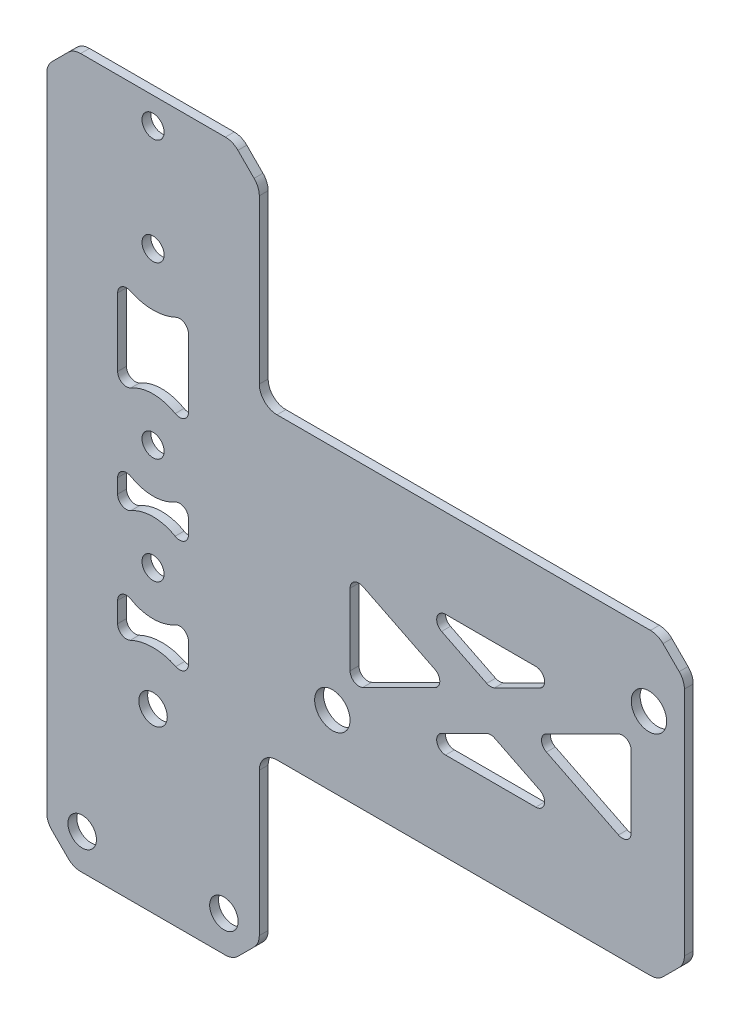
SolidWorks part; units mm, degrees
ref_plane "Front Plane" through (0, 0, 0) normal (0, 0, 1) x (1, 0, 0)
ref_plane "Top Plane" through (0, 0, 0) normal (0, 1, 0) x (1, 0, 0)
ref_plane "Right Plane" through (0, 0, 0) normal (1, 0, 0) x (0, 0, -1)
sketch "Sketch1" plane through (0, 0, 0) normal (0, 0, 1) x (1, 0, 0)
  line L1 (-19.05, 63.5) -> (19.05, 63.5)
  line L2 (-19.05, 63.5) -> (-19.05, -63.5)
  line L3 (-19.05, -63.5) -> (19.05, -63.5)
  line L4 (19.05, 63.5) -> (19.05, -63.5)
  line L5 (-19.05, 63.5) -> (19.05, -63.5) construction
  line L6 (-19.05, -63.5) -> (19.05, 63.5) construction
  line L7 (19.05, 25.019) -> (95.25, 25.019)
  line L8 (19.05, 25.019) -> (19.05, -28.575)
  line L9 (19.05, -28.575) -> (95.25, -28.575)
  line L10 (95.25, 25.019) -> (95.25, -28.575)
  circle A0 centre (32.1437, -15.875) radius 3.175
  circle A1 centre (88.9, 12.319) radius 3.175
  point P0 (0, 0)
  dimension "D7" = 6.35
  dimension "D1" = 34.925
  dimension "D2" = 38.1
  dimension "D3" = 76.2
  dimension "D4" = 127
  dimension "D5" = 6.35
  dimension "D6" = 12.7
  dimension "D8" = 12.7
  dimension "D9" = 56.7563
  dimension "D10" = 63.3733
extrude "Boss-Extrude1" add sketch "Sketch1" along normal mid plane 1.5875 contours L10 L7 L4 L9 A1 A0 | L4 L1 L2 L3
sketch "Sketch2" plane through (0, 0, 0.7937) normal (0, 0, 1) x (1, 0, 0)
  line L1 (-12.7, -57.15) -> (12.7, -57.15) construction
  line L2 (-19.05, -63.5) -> (19.05, -63.5) construction
  circle A0 centre (-12.7, -57.15) radius 2.5527
  circle A1 centre (12.7, -57.15) radius 2.5527
  circle A2 centre (0, -31.75) radius 2.5527
  circle A3 centre (0, -9.8425) radius 1.9812
  circle A4 centre (0, 9.2075) radius 1.9812
  circle A5 centre (0, 39.6875) radius 1.9812
  circle A6 centre (0, 58.7375) radius 1.9812
  point P14 (0, -57.15)
  dimension "D1" = 3.9624
  dimension "D2" = 5.1054
  dimension "D3" = 25.4
  dimension "D4" = 25.4
  dimension "D5" = 21.9075
  dimension "D6" = 6.35
  dimension "D7" = 19.05
  dimension "D8" = 30.48
  dimension "D9" = 19.05
extrude "Cut-Extrude1" cut sketch "Sketch2" against normal through all
sketch "Sketch3" plane through (0, 0, 0.7937) normal (0, 0, 1) x (1, 0, 0)
  line L0 (35.3187, -12.7) -> (85.725, -12.7)
  line L1 (32.1437, 12.319) -> (88.9, 12.319)
  line L2 (32.1437, 12.319) -> (32.1437, -15.875)
  line L3 (32.1437, -15.875) -> (88.9, -15.875)
  line L4 (88.9, 12.319) -> (88.9, -15.875)
  line L5 (32.1437, 12.319) -> (88.9, -15.875) construction
  line L6 (32.1437, -15.875) -> (88.9, 12.319) construction
  line L7 (85.725, 9.144) -> (85.725, -12.7)
  line L8 (35.3187, 9.144) -> (85.725, 9.144)
  line L9 (35.3187, 9.144) -> (35.3187, -12.7)
  line L10 (30.7312, 9.4755) -> (87.4875, -18.7185)
  line L11 (33.5562, -18.7185) -> (90.3125, 9.4755)
  line L12 (33.5562, 15.1625) -> (90.3125, -13.0315)
  line L13 (30.7312, -13.0315) -> (87.4875, 15.1625)
  circle A0 centre (32.1437, -15.875) radius 3.175 construction
  point P0 (60.5219, -1.778)
  dimension "D1" = 3.175
  dimension "D2" = 3.175
  dimension "D3" = 3.175
extrude "Cut-Extrude2" cut sketch "Sketch3" against normal through all contours L12 L13 L8 | L9 L13 L10 | L11 L0 L10 | L11 L12 L7
fillet "Fillet2" radius 1.5875 12 edges at (60.5219, -5.3232, 0) (75.3719, -12.7, 0) (75.3719, 9.144, 0) (45.6718, 9.144, 0) (60.5218, 1.7672, 0) (85.725, 7.1966, 0) (85.725, -10.7526, 0) (67.6585, -1.778, 0) (45.6718, -12.7, 0) (53.3852, -1.778, 0) (35.3187, 7.1966, 0) (35.3187, -10.7526, 0)
chamfer "Chamfer1" distance 4.7625 angle 45 6 edges at (95.25, 25.019, 0) (95.25, -28.575, 0) (19.05, -63.5, 0) (-19.05, -63.5, 0) (19.05, 63.5, 0) (-19.05, 63.5, 0)
fillet "Fillet3" radius 3.175 14 edges at (95.25, -23.8125, 0) (90.4875, -28.575, 0) (19.05, -28.575, 0) (14.2875, -63.5, 0) (-14.2875, -63.5, 0) (-19.05, -58.7375, 0) (-19.05, 58.7375, 0) (-14.2875, 63.5, 0) (14.2875, 63.5, 0) (19.05, 58.7375, 0) (19.05, 25.019, 0) (90.4875, 25.019, 0) (95.25, 20.2565, 0) (19.05, -58.7375, 0)
sketch "Sketch5" plane through (0, 0, 0.7937) normal (0, 0, 1) x (1, 0, 0)
  line L28 (82.55, -15.875) -> (82.55, 12.319)
  line L29 (82.55, 12.319) -> (22.225, 12.319)
  line L30 (6.35, 28.194) -> (6.35, 50.8)
  line L31 (6.35, -24.6505) -> (6.35, 50.8)
  line L32 (-6.35, 50.8) -> (-6.35, -50.8)
  line L33 (6.35, 50.8) -> (-6.35, 50.8)
  line L34 (6.35, 50.8) -> (-6.35, 50.8)
  line L35 (22.225, -15.875) -> (82.55, -15.875)
  line L36 (82.55, -15.875) -> (82.55, 12.319)
  line L37 (82.55, 12.319) -> (22.225, 12.319)
  line L38 (-6.35, -50.8) -> (6.35, -50.8)
  line L39 (-6.35, -50.8) -> (6.35, -50.8)
  line L40 (-6.35, 50.8) -> (-6.35, -50.8)
  line L41 (6.35, -50.8) -> (6.35, -31.75)
  line L42 (6.35, -50.8) -> (6.35, -24.6505)
  line L43 (22.225, -15.875) -> (82.55, -15.875)
  circle A14 centre (0, 39.6875) radius 9.525
  circle A15 centre (0, 9.2075) radius 7.9375
  circle A16 centre (0, -9.8425) radius 7.9375
  circle A17 centre (0, -31.75) radius 9.525
  arc A28 (6.35, 28.194) -> (22.225, 12.319) centre (22.225, 28.194) ccw
  arc A29 (22.225, -15.875) -> (6.35, -31.75) centre (22.225, -31.75) ccw
  arc A30 (6.35, 28.194) -> (22.225, 12.319) centre (22.225, 28.194) ccw
  arc A31 (22.225, -15.875) -> (6.35, -31.75) centre (22.225, -31.75) ccw
  dimension "D2" = 19.05
  dimension "D3" = 19.05
  dimension "D4" = 15.875
  dimension "D1" = 12.7
extrude "Cut-Extrude3" cut sketch "Sketch5" against normal through all contours A17 L31 A16 L40 | A16 L31 A15 L40 | A15 L31 A14 L40
fillet "Fillet5" radius 1.5875 12 edges at (-6.35, -14.605, 0) (-6.35, -5.08, 0) (6.35, -14.605, 0) (6.35, -5.08, 0) (6.35, -24.6505, 0) (-6.35, -24.6505, 0) (-6.35, 4.445, 0) (-6.35, 13.97, 0) (6.35, 4.445, 0) (6.35, 13.97, 0) (-6.35, 32.588, 0) (6.35, 32.588, 0)
